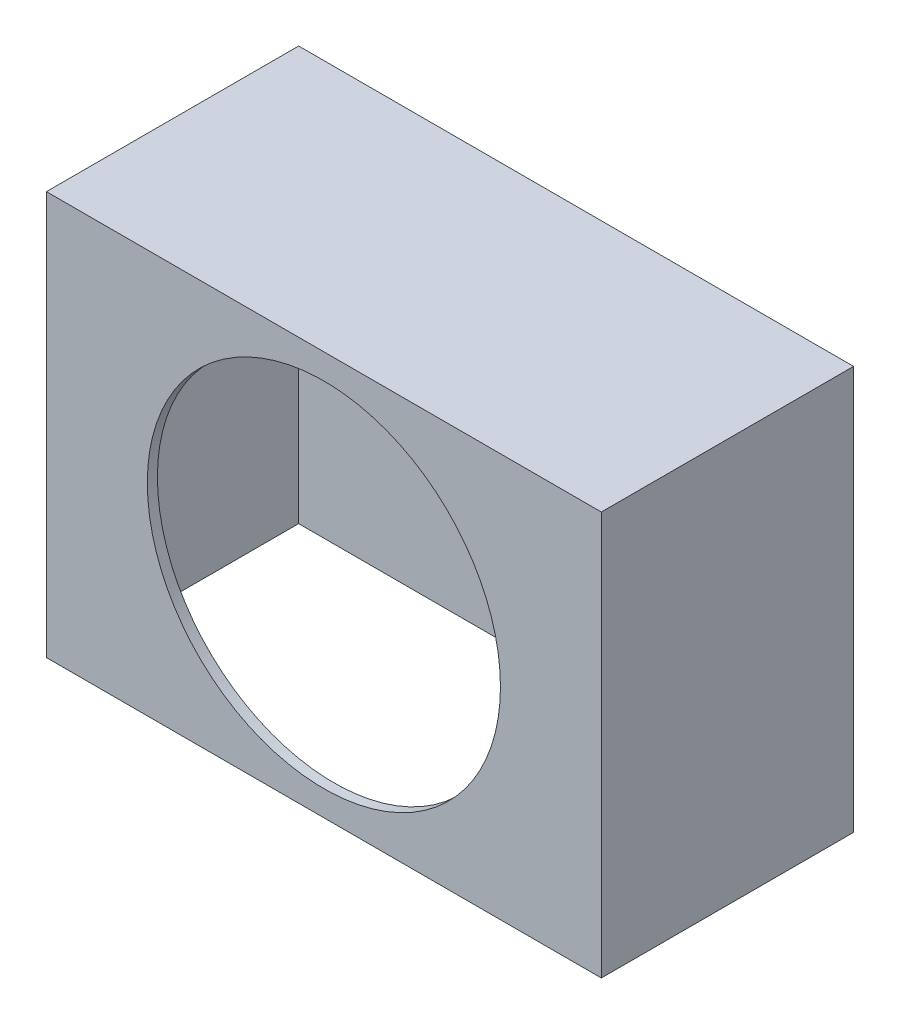
SolidWorks part; units mm, degrees
ref_plane "前视基准面" through (0, 0, 0) normal (0, 0, 1) x (1, 0, 0)
ref_plane "上视基准面" through (0, 0, 0) normal (0, 1, 0) x (1, 0, 0)
ref_plane "右视基准面" through (0, 0, 0) normal (1, 0, 0) x (0, 0, -1)
sketch "草图1" plane through (0, 0, 0) normal (0, 1, 0) x (1, 0, 0)
  line L1 (55, -25) -> (-55, -25)
  line L2 (55, -25) -> (55, 25)
  line L3 (55, 25) -> (-55, 25)
  line L4 (-55, -25) -> (-55, 25)
  line L5 (55, -25) -> (-55, 25) construction
  line L6 (55, 25) -> (-55, -25) construction
  point P0 (0, 0)
  dimension "D1" = 110
  dimension "D2" = 50
extrude "凸台-拉伸1" add sketch "草图1" along normal blind 80
shell "抽壳1" thickness 2
sketch "草图2" plane through (0, 0, 25) normal (0, 0, 1) x (1, 0, 0)
  circle A0 centre (0, 40) radius 35
  dimension "D1" = 70
extrude "切除-拉伸1" cut sketch "草图2" against normal blind 2
